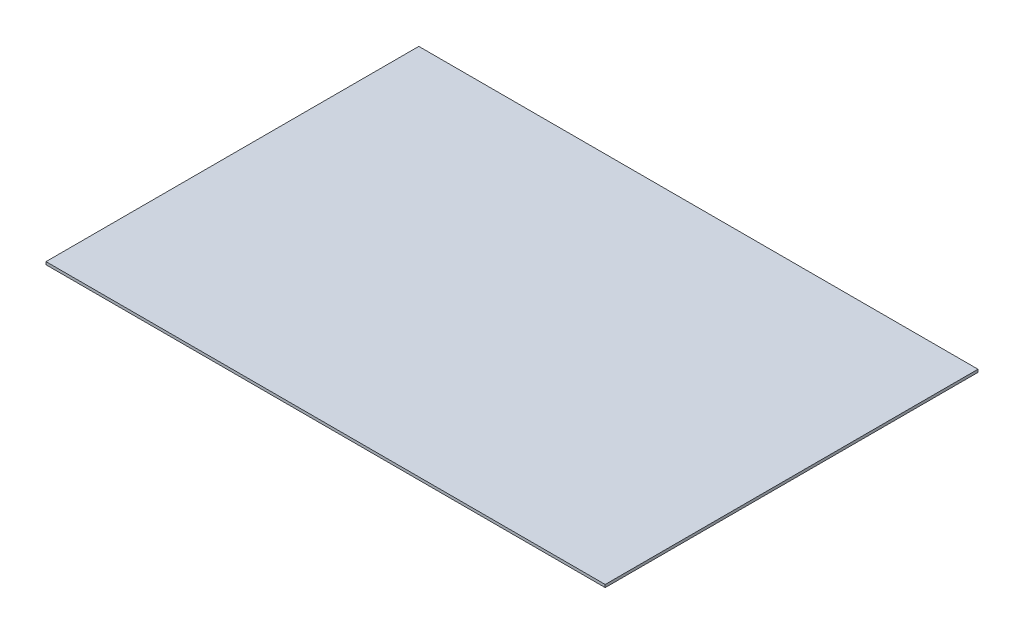
SolidWorks part; units mm, degrees
ref_plane "Front Plane" through (0, 0, 0) normal (0, 0, 1) x (1, 0, 0)
ref_plane "Top Plane" through (0, 0, 0) normal (0, 1, 0) x (1, 0, 0)
ref_plane "Right Plane" through (0, 0, 0) normal (1, 0, 0) x (0, 0, -1)
sketch "Sketch1" plane through (0, 0, 0) normal (0, 1, 0) x (1, 0, 0)
  line L1 (-152.4, -101.6) -> (152.4, -101.6)
  line L2 (-152.4, -101.6) -> (-152.4, 101.6)
  line L3 (-152.4, 101.6) -> (152.4, 101.6)
  line L4 (152.4, -101.6) -> (152.4, 101.6)
  line L5 (-152.4, -101.6) -> (152.4, 101.6) construction
  line L6 (-152.4, 101.6) -> (152.4, -101.6) construction
  point P0 (0, 0)
  dimension "D1" = 304.8
  dimension "D2" = 203.2
extrude "Boss-Extrude1" add sketch "Sketch1" along normal blind 1.5
